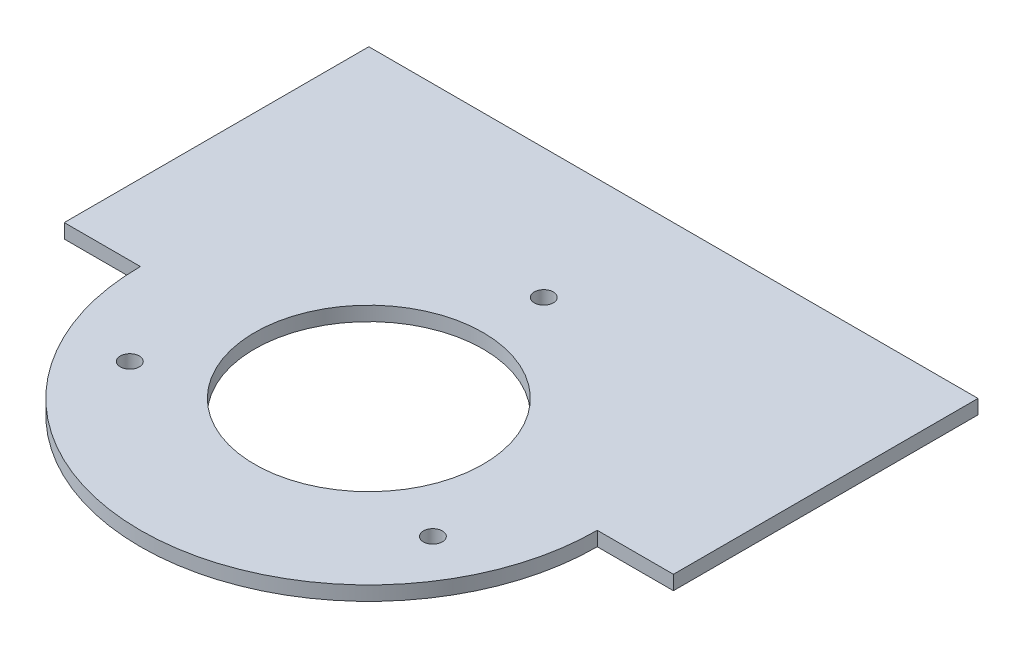
SolidWorks part; units mm, degrees
ref_plane "Front Plane" through (0, 0, 0) normal (0, 0, 1) x (1, 0, 0)
ref_plane "Top Plane" through (0, 0, 0) normal (0, 1, 0) x (1, 0, 0)
ref_plane "Right Plane" through (0, 0, 0) normal (1, 0, 0) x (0, 0, -1)
sketch "Sketch1" plane through (0, 0, 0) normal (0, 1, 0) x (1, 0, 0)
  line L0 (0, 0) -> (0, 58.3655) construction
  line L1 (0, 0) -> (-50.546, -29.1827) construction
  line L2 (0, 0) -> (50.546, -29.1827) construction
  line L3 (-101.6, 0) -> (-101.6, 101.6)
  line L4 (-101.6, 101.6) -> (101.6, 101.6)
  line L5 (101.6, 101.6) -> (101.6, 0)
  line L6 (-101.6, 76.2) -> (101.6, 76.2) construction
  line L7 (-76.2, 0) -> (-101.6, 0)
  line L8 (76.2, 0) -> (101.6, 0)
  circle A0 centre (0, 0) radius 58.3655 construction
  circle A1 centre (0, 58.3655) radius 3.175
  circle A2 centre (-50.546, -29.1827) radius 3.175
  circle A3 centre (50.546, -29.1827) radius 3.175
  circle A4 centre (0, 0) radius 38.1
  arc A5 (-76.2, 0) -> (76.2, 0) centre (0, 0) cw construction
  arc A7 (-76.2, 0) -> (76.2, 0) centre (0, 0) ccw
  point P16 (0, 101.6)
  dimension "D1" = 101.092
  dimension "D4" = 6.35
  dimension "D5" = 76.2
  dimension "D6" = 203.2
  dimension "D8" = 76.2
  dimension "D2" = 120
  dimension "D3" = 120
  dimension "D7" = 25.4
  dimension "D9" = 101.6
extrude "Boss-Extrude1" add sketch "Sketch1" along normal blind 4.7625
